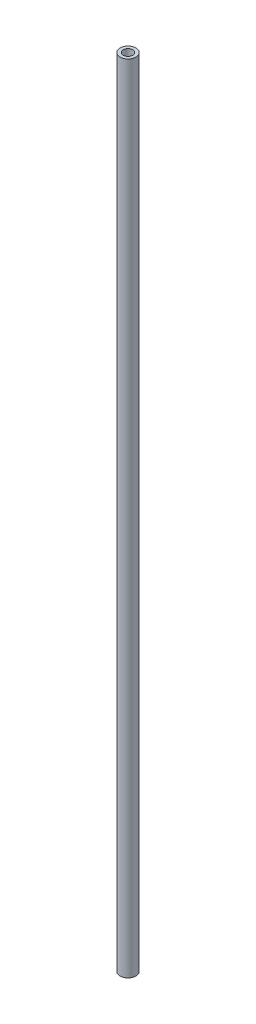
SolidWorks part; units mm, degrees
ref_plane "前视基准面" through (0, 0, 0) normal (0, 0, 1) x (1, 0, 0)
ref_plane "上视基准面" through (0, 0, 0) normal (0, 1, 0) x (1, 0, 0)
ref_plane "右视基准面" through (0, 0, 0) normal (1, 0, 0) x (0, 0, -1)
sketch "草图1" plane through (0, 0, 0) normal (0, 1, 0) x (1, 0, 0)
  circle A0 centre (0, 0) radius 1.5
  circle A1 centre (0, 0) radius 2.5
  dimension "D1" = 3
  dimension "D2" = 5
extrude "凸台-拉伸1" add sketch "草图1" along normal blind 250
